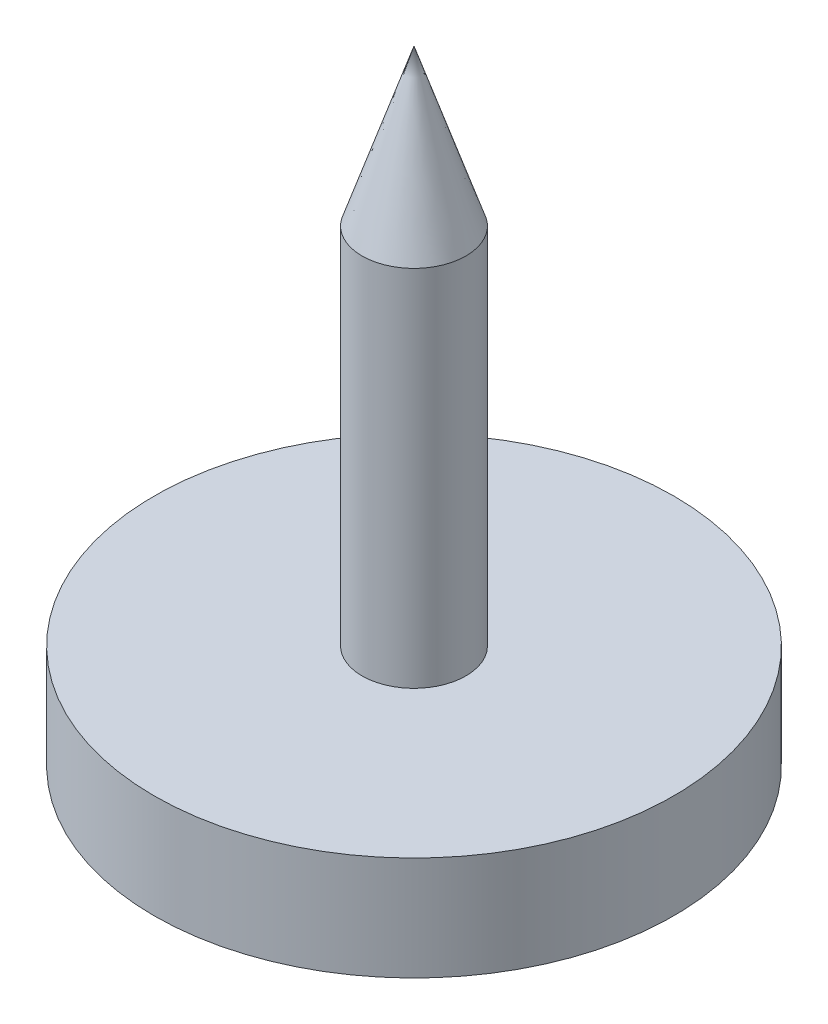
SolidWorks part; units mm, degrees
ref_plane "前视基准面" through (0, 0, 0) normal (0, 0, 1) x (1, 0, 0)
ref_plane "上视基准面" through (0, 0, 0) normal (0, 1, 0) x (1, 0, 0)
ref_plane "右视基准面" through (0, 0, 0) normal (1, 0, 0) x (0, 0, -1)
sketch "草图2" plane through (0, 0, 0) normal (0, 1, 0) x (1, 0, 0)
  circle A0 centre (0, 0) radius 50
  dimension "D1" = 100
extrude "凸台-拉伸1" add sketch "草图2" along normal blind 20
sketch "草图3" plane through (0, 20, 0) normal (0, 1, 0) x (1, 0, 0)
  circle A0 centre (0, 0) radius 10
  dimension "D1" = 20
extrude "凸台-拉伸2" add sketch "草图3" along normal blind 70
sketch "草图4" plane through (0, 0, 0) normal (0, 0, 1) x (1, 0, 0)
  line L0 (0, 0) -> (0, 133.1536) construction
  line L1 (-50, 0) -> (50, 0) construction
  line L2 (0, 90) -> (10, 90)
  line L3 (10, 90) -> (-10, 90) construction
  line L4 (0, 90) -> (0, 120)
  line L5 (0, 120) -> (10, 90)
  dimension "D1" = 30
revolve "旋转1" add sketch "草图4" angle 360 about L0
